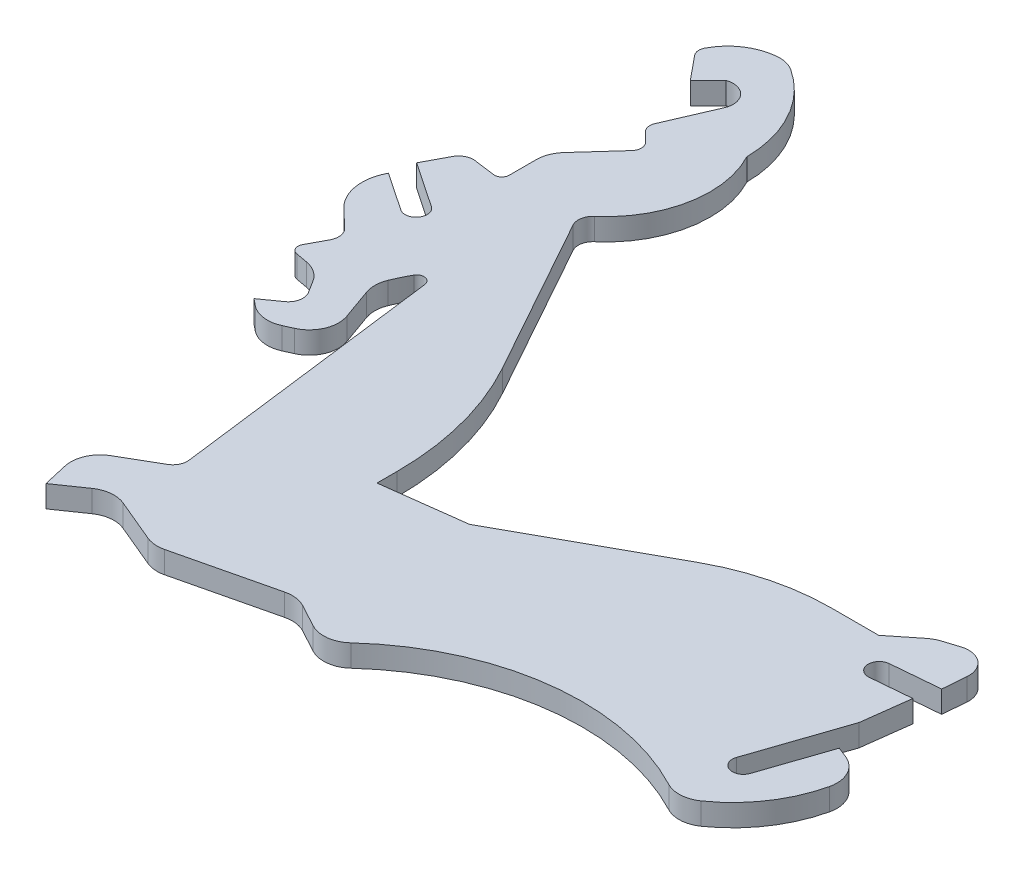
SolidWorks part; units mm, degrees
ref_plane "Front Plane" through (0, 0, 0) normal (0, 0, 1) x (1, 0, 0)
ref_plane "Top Plane" through (0, 0, 0) normal (0, 1, 0) x (1, 0, 0)
ref_plane "Right Plane" through (0, 0, 0) normal (1, 0, 0) x (0, 0, -1)
sketch "Sketch2" plane through (0, 0, 0) normal (0, 1, 0) x (1, 0, 0)
  line L0 (104.8617, 51.61) -> (96.2857, 51.61)
  line L1 (96.2857, 48.61) -> (104.8617, 48.61)
  line L2 (104.8617, 48.61) -> (104.8617, 42.36)
  line L3 (107.0706, 39.34) -> (104.0266, 29.4584)
  line L4 (101.1595, 30.3416) -> (104.8617, 42.36)
  line L5 (105.5312, 18.3607) -> (111.09, 27.1258)
  line L6 (104.8617, 51.61) -> (107.0706, 55.46)
  line L7 (89.7728, 69.8362) -> (57.4, 86.17)
  line L8 (41.6529, 73.6621) -> (36.03, 31.3784)
  line L9 (36.03, 31.3784) -> (29.1482, 28.9869)
  line L10 (29.1482, 28.9869) -> (21.9915, 21.0198)
  line L11 (21.9915, 21.0198) -> (8.1869, 15.1615)
  line L12 (0, 0) -> (0, 4.28)
  line L13 (0, 4.28) -> (8.2554, 5.2)
  line L14 (7.9231, 8.1815) -> (-3.1214, 6.9507)
  line L15 (-3.1214, 6.9507) -> (-7.4992, 8.4826)
  line L16 (-7.4992, 8.4826) -> (-11.8276, 7.2216)
  line L17 (-11.8276, 7.2216) -> (-19.2552, 11.2976)
  line L18 (-19.2552, 11.2976) -> (-23.2053, 10.8574)
  line L19 (-23.2053, 10.8574) -> (-22.2697, 7.6463)
  line L20 (-22.2697, 7.6463) -> (-24.8125, 7.2216)
  line L21 (0, 0) -> (20.16, 0)
  line L22 (20.16, 0) -> (27.0155, 3.9247)
  line L23 (27.0155, 3.9247) -> (38.9, -1.2)
  line L24 (38.9, -1.2) -> (41.66, 2.4827)
  line L25 (41.66, 2.4827) -> (45.9, 1.9915)
  line L26 (45.9, 1.9915) -> (46.4657, 5.8541)
  line L27 (25.83, 11.99) -> (49.95, 19.39)
  line L28 (49.95, 19.39) -> (57.13, 16.32)
  line L29 (57.13, 16.32) -> (61.9358, 23.0276)
  line L30 (61.9358, 23.0276) -> (67.6517, 44.29)
  arc A0 (96.2857, 51.61) -> (96.2857, 48.61) centre (96.2857, 50.11) ccw
  arc A1 (107.0706, 39.34) -> (111.09, 27.1258) centre (97.2099, 29.3266) cw
  arc A2 (104.0266, 29.4584) -> (101.1595, 30.3416) centre (102.5931, 29.9) cw
  arc A3 (107.0706, 55.46) -> (93.2591, 66.4439) centre (93.6334, 52.7391) ccw
  arc A4 (93.2591, 66.4439) -> (89.7728, 69.8362) centre (93.1665, 69.8362) cw
  arc A5 (57.4, 86.17) -> (41.6529, 73.6621) centre (56.0104, 71.7528) ccw
  arc A6 (8.1869, 15.1615) -> (-17.7049, 14.5311) centre (-5.6083, 49.7338) cw
  arc A7 (8.2554, 5.2) -> (7.9231, 8.1815) centre (8.0892, 6.6908) ccw
  arc A8 (-24.8125, 7.2216) -> (-27.5, 15.12) centre (-19.6156, 13.3963) cw
  arc A9 (-27.5, 15.12) -> (-17.7049, 14.5311) centre (-22.91, 9.71) cw
  arc A10 (46.4657, 5.8541) -> (26.4315, 9.0647) centre (30.5748, -29.1928) ccw
  arc A11 (26.4315, 9.0647) -> (25.83, 11.99) centre (26.27, 10.556) cw
  arc A12 (67.6517, 44.29) -> (105.5312, 18.3607) centre (122.4523, 83.7134) ccw
  point P4 (0, 0)
  point P9 (102.1515, 28.4665)
  point P12 (94.7857, 50.11)
  point P13 (-27.5, 15.12)
  point P72 (9.58, 6.8569)
  dimension "D6" = 1.5
  dimension "D11" = 1.5
  dimension "D32" = 14.0535
  dimension "D33" = 13.7098
  dimension "D34" = 3.3937
  dimension "D35" = 14.484
  dimension "D36" = 37.223
  dimension "D37" = 8.0706
  dimension "D38" = 7.0948
  dimension "D39" = 38.4812
  dimension "D40" = 67.5078
  dimension "D75" = 1.5
  dimension "D1" = 51.61
  dimension "D2" = 111.09
  dimension "D3" = 10.076
  dimension "D4" = 27.5
  dimension "D5" = 15.12
  dimension "D7" = 29.9
  dimension "D8" = 39.34
  dimension "D9" = 6.25
  dimension "D10" = 102.5931
  dimension "D12" = 4.28
  dimension "D13" = 20.16
  dimension "D14" = 5.14
  dimension "D15" = 1.2
  dimension "D16" = 45.9
  dimension "D17" = 38.9
  dimension "D18" = 86.17
  dimension "D19" = 9.58
  dimension "D20" = 5.2
  dimension "D21" = 11.99
  dimension "D22" = 16.32
  dimension "D23" = 57.13
  dimension "D24" = 49.95
  dimension "D25" = 26.27
  dimension "19.39" = 19.39
  dimension "D26" = 84.9
  dimension "D27" = 63.53
  dimension "D28" = 37.21
  dimension "D29" = 44.29
  dimension "D30" = 3.85
  dimension "D31" = 20
  dimension "D41" = 8.1869
  dimension "D42" = 21.9915
  dimension "D43" = 26.4315
  dimension "D44" = 27.0155
  dimension "D45" = 29.1482
  dimension "D46" = 41.6529
  dimension "D47" = 41.66
  dimension "D48" = 46.4657
  dimension "D49" = 56.0104
  dimension "D50" = 61.9358
  dimension "D51" = 67.6517
  dimension "D52" = 89.7728
  dimension "D53" = 97.2099
  dimension "D54" = 105.5312
  dimension "D55" = 122.4523
  dimension "D56" = 3.1214
  dimension "D57" = 5.6083
  dimension "D58" = 7.4992
  dimension "D59" = 11.8276
  dimension "D60" = 17.7049
  dimension "D61" = 19.2552
  dimension "D62" = 19.6156
  dimension "D63" = 22.2697
  dimension "D64" = 22.91
  dimension "D65" = 23.2053
  dimension "D66" = 24.8125
  dimension "D67" = 1.9915
  dimension "D68" = 2.4827
  dimension "D69" = 7.6463
  dimension "D70" = 8.4826
  dimension "D71" = 11.2976
  dimension "D72" = 21.0198
  dimension "D73" = 23.0276
  dimension "D74" = 28.9869
sketch "Sketch3" plane through (0, 0, 0) normal (0, 1, 0) x (1, 0, 0)
  line L0 (7.9231, 8.1815) -> (1.2884, 7.4422)
  line L1 (45.9, 1.9915) -> (46.4657, 5.8541) construction
  line L2 (41.66, 2.4827) -> (45.9, 1.9915) construction
  line L3 (38.9, -1.2) -> (41.66, 2.4827) construction
  line L4 (27.0155, 3.9247) -> (38.9, -1.2) construction
  line L5 (20.16, 0) -> (27.0155, 3.9247) construction
  line L6 (0, 4.28) -> (8.2554, 5.2) construction
  line L7 (0, 0) -> (0, 4.28) construction
  line L8 (0, 0) -> (20.16, 0) construction
  line L9 (1.2884, 7.4422) -> (2.7682, 14.19)
  line L10 (45.9, 1.9915) -> (46.4657, 5.8541)
  line L11 (41.66, 2.4827) -> (45.9, 1.9915)
  line L12 (38.9, -1.2) -> (41.66, 2.4827)
  line L13 (27.0155, 3.9247) -> (38.9, -1.2)
  line L14 (20.16, 0) -> (27.0155, 3.9247)
  line L15 (0, 4.28) -> (8.2554, 5.2)
  line L16 (0, 0) -> (0, 4.28)
  line L17 (0, 0) -> (20.16, 0)
  line L18 (-19.3597, 16.8) -> (-22.2168, 13.6663)
  line L19 (-22.2168, 13.6663) -> (-24.8203, 14.623)
  line L20 (-24.8203, 14.623) -> (-22.6465, 20.5386)
  line L21 (-22.6465, 20.5386) -> (-15.7038, 22.1118)
  line L22 (-15.7038, 22.1118) -> (-10.0733, 18.8185)
  line L23 (-10.0733, 18.8185) -> (-5.1865, 19.8808)
  line L24 (-5.1865, 19.8808) -> (12.13, 16.8)
  line L25 (12.13, 16.8) -> (38.76, 34.29)
  line L26 (87.31, 93.5914) -> (80.7227, 93.015)
  line L27 (80.9841, 90.0265) -> (86.4632, 90.5058)
  line L28 (87.31, 93.5914) -> (87.31, 111.63)
  line L29 (87.31, 111.63) -> (66.29, 103.0079)
  line L32 (66.29, 103.0079) -> (64.5523, 69.7569)
  line L33 (64.5523, 69.7569) -> (56.0586, 66.407)
  line L34 (56.0586, 66.407) -> (44.7, 32)
  line L35 (44.7, 32) -> (38.76, 34.29)
  line L36 (25.83, 11.99) -> (54.05, 24.15)
  line L37 (54.05, 24.15) -> (66.29, 24.15)
  line L38 (68.0387, 28.663) -> (60.2978, 29.686)
  line L39 (87.31, 79.61) -> (91.6185, 77.8876)
  line L40 (87.31, 79.61) -> (84.2303, 70.5437)
  line L41 (81.3897, 71.5086) -> (85.6329, 84)
  line L42 (85.6329, 84) -> (86.4632, 90.5058)
  arc A0 (25.83, 11.99) -> (26.4315, 9.0647) centre (26.27, 10.556) ccw construction
  arc A1 (46.4657, 5.8541) -> (26.4315, 9.0647) centre (30.5748, -29.1928) ccw construction
  arc A3 (25.83, 11.99) -> (26.4315, 9.0647) centre (26.27, 10.556) ccw
  arc A4 (46.4657, 5.8541) -> (26.4315, 9.0647) centre (30.5748, -29.1928) ccw
  arc A5 (8.2554, 5.2) -> (7.9231, 8.1815) centre (8.0892, 6.6908) ccw
  arc A6 (2.7682, 14.19) -> (-19.3597, 16.8) centre (-1.1426, 76.1401) cw
  arc A7 (80.7227, 93.015) -> (80.9841, 90.0265) centre (80.8534, 91.5207) ccw
  arc A8 (66.29, 24.15) -> (68.0387, 28.663) centre (61.3409, 28.663) ccw
  arc A9 (60.2978, 29.686) -> (80.9841, 62.2084) centre (34.8127, 68.7363) ccw
  arc A10 (91.6185, 77.8876) -> (80.9841, 62.2084) centre (74.0824, 78.3355) cw
  arc A11 (84.2303, 70.5437) -> (81.3897, 71.5086) centre (82.81, 71.0261) cw
  point P20 (87.31, 111.63)
  point P28 (87.31, 79.61)
  point P40 (79.3591, 91.39)
  point P55 (0, 2.14)
  point P77 (9.58, 6.8569)
  point P90 (82.3275, 69.6058)
  dimension "D5" = 1.5
  dimension "D22" = 62.0734
  dimension "D23" = 6.6978
  dimension "D24" = 46.6306
  dimension "D25" = 17.5418
  dimension "D1" = 111.63
  dimension "D2" = 87.31
  dimension "D3" = 79.61
  dimension "D4" = 17.97
  dimension "D6" = 8.25
  dimension "95" = 95
  dimension "D7" = 54.05
  dimension "D8" = 44.7
  dimension "D9" = 32
  dimension "D10" = 24.15
  dimension "D11" = 16.8
  dimension "D12" = 2.55
  dimension "D13" = 38.76
  dimension "D14" = 2.29
  dimension "D15" = 66.29
  dimension "D16" = 4.64
  dimension "D17" = 23.46
  dimension "D18" = 82.81
  dimension "D19" = 84
  dimension "D20" = 5.5
  dimension "D21" = 14.19
  dimension "D26" = 1.2884
  dimension "D27" = 2.7682
  dimension "D28" = 34.8127
  dimension "D29" = 56.0586
  dimension "D30" = 60.2978
  dimension "D31" = 61.3409
  dimension "D32" = 64.5523
  dimension "D33" = 68.0387
  dimension "D34" = 74.0824
  dimension "D35" = 1.1426
  dimension "D36" = 13.6663
  dimension "D37" = 14.623
  dimension "D38" = 91.6185
  dimension "D39" = 18.8185
  dimension "D40" = 5.1865
  dimension "D41" = 10.0733
  dimension "D42" = 15.7038
  dimension "D43" = 19.8808
  dimension "D44" = 22.2168
  dimension "D45" = 22.6465
  dimension "D46" = 24.8203
  dimension "D48" = 22.1118
  dimension "D49" = 66.407
  dimension "D51" = 69.7569
  dimension "D53" = 103.0079
sketch "Sketch4" plane through (0, 0, 0) normal (0, 1, 0) x (1, 0, 0)
  line L0 (87.31, 79.61) -> (91.6185, 77.8876) construction
  line L1 (87.31, 79.61) -> (84.2303, 70.5437) construction
  line L2 (81.3897, 71.5086) -> (85.6329, 84) construction
  line L3 (85.6329, 84) -> (86.4632, 90.5058) construction
  line L4 (87.31, 93.5914) -> (80.7227, 93.015) construction
  line L5 (80.9841, 90.0265) -> (86.4632, 90.5058) construction
  line L6 (87.31, 79.61) -> (91.6185, 77.8876)
  line L7 (87.31, 79.61) -> (84.2303, 70.5437)
  line L8 (81.3897, 71.5086) -> (85.6329, 84)
  line L9 (85.6329, 84) -> (86.4632, 90.5058)
  line L10 (87.31, 93.5914) -> (80.7227, 93.015)
  line L11 (80.9841, 90.0265) -> (86.4632, 90.5058)
  line L12 (87.31, 93.5914) -> (87.9384, 101.2314)
  line L13 (87.9384, 101.2314) -> (80.8847, 99.0137)
  line L14 (80.8847, 99.0137) -> (76.6618, 95.6406)
  line L15 (76.6618, 95.6406) -> (62.4514, 95.6406)
  line L16 (62.4514, 95.6406) -> (35.6224, 80.8332)
  line L17 (35.6224, 80.8332) -> (24.4232, 79.3958)
  line L18 (24.4232, 79.3958) -> (24.4232, 92.5302)
  line L19 (24.4232, 92.5302) -> (6.4632, 124.7958)
  line L20 (39.5557, 56.754) -> (32.4992, 60.5705)
  line L21 (32.4992, 60.5705) -> (16.5173, 56.754)
  line L22 (16.5173, 56.754) -> (7.4148, 60.5705)
  line L23 (7.4148, 60.5705) -> (1.8925, 56.754)
  line L24 (1.8925, 56.754) -> (0.4632, 62.9924)
  line L25 (0.4632, 62.9924) -> (9.066, 67.9678)
  line L26 (9.066, 67.9678) -> (3.8794, 108.8404)
  line L27 (0.6632, 102.6159) -> (3.8794, 93.5914)
  line L28 (3.8794, 93.5914) -> (-2.9368, 90.5058)
  line L29 (-2.9368, 90.5058) -> (-5.7689, 92.8083)
  line L30 (-5.7689, 92.8083) -> (-1.7781, 95.6406)
  line L31 (-1.7781, 95.6406) -> (-4.7653, 100.4083)
  line L32 (-4.7653, 100.4083) -> (-9.4961, 101.2694)
  line L33 (-9.4961, 101.2694) -> (-6.8152, 106.2905)
  line L34 (-6.8152, 106.2905) -> (-13.5555, 112.677)
  line L35 (-13.5555, 112.677) -> (-11.4183, 116.8058)
  line L36 (-11.4183, 116.8058) -> (-6.2216, 113.3058)
  line L37 (-4.5458, 115.7941) -> (-10.725, 119.9558)
  line L38 (-10.725, 119.9558) -> (-8.366, 124.3875)
  line L39 (-8.366, 124.3875) -> (-2.9368, 123.667)
  line L40 (-2.9368, 123.667) -> (-2.9368, 130.0558)
  line L41 (-2.9368, 130.0558) -> (3.4131, 137.0856)
  line L42 (3.4131, 137.0856) -> (0.5228, 139.9564)
  line L43 (0.5228, 139.9564) -> (3.6981, 147.3182)
  line L44 (0.6632, 150.8114) -> (-1.7781, 148.37)
  line L45 (-1.7781, 148.37) -> (-4.9998, 152.3019)
  arc A0 (-6.2216, 113.3058) -> (-4.5458, 115.7941) centre (-5.3837, 114.5499) ccw
  arc A1 (81.3897, 71.5086) -> (84.2303, 70.5437) centre (82.81, 71.0261) ccw construction
  arc A2 (80.7227, 93.015) -> (80.9841, 90.0265) centre (80.8534, 91.5207) ccw construction
  arc A3 (91.6185, 77.8876) -> (81.8558, 62.61) centre (74.0824, 78.3355) cw
  arc A4 (81.3897, 71.5086) -> (84.2303, 70.5437) centre (82.81, 71.0261) ccw
  arc A5 (80.7227, 93.015) -> (80.9841, 90.0265) centre (80.8534, 91.5207) ccw
  arc A6 (80.9841, 62.2084) -> (91.6185, 77.8876) centre (74.0824, 78.3355) ccw construction
  arc A7 (81.8558, 62.61) -> (39.5557, 56.754) centre (64.2679, 33.9509) ccw
  arc A8 (3.8794, 108.8404) -> (0.6632, 102.6159) centre (21.1237, 95.9873) ccw
  arc A9 (6.4632, 124.7958) -> (11.0968, 143.2092) centre (-1.4543, 136.5779) ccw
  arc A10 (11.0968, 143.2092) -> (2.7832, 157.1114) centre (-4.9998, 143.0202) ccw
  arc A11 (3.6981, 147.3182) -> (0.6632, 150.8114) centre (1.4835, 148.4591) ccw
  arc A12 (-4.9998, 152.3019) -> (2.7832, 157.1114) centre (1.9469, 149.7625) cw
  point P0 (91.6185, 77.8876)
  point P22 (2.7832, 157.1114)
  point P24 (0.6632, 150.8114)
  point P25 (-2.9368, 90.5058)
  point P26 (24.4232, 79.3958)
  point P27 (6.4632, 124.7958)
  point P31 (37.6632, 57.2558)
  point P70 (-2.9368, 130.365)
  point P71 (-2.9368, 130.0558)
  point P72 (-13.5555, 112.677)
  point P74 (5.2836, 108.8946)
  point P75 (8.4935, 71.0261)
  point P76 (9.066, 67.9678)
  point P77 (12.229, 60.1104)
  point P78 (7.7636, 59.0479)
  point P79 (16.8662, 55.2315)
  point P80 (0, 0)
  point P81 (0, 0)
  point P82 (35.6224, 80.8332)
  point P83 (3.8794, 106.2905)
  point P85 (0, 0)
  point P86 (5.0821, 105.6005)
  point P87 (0.4632, 100.4083)
  point P88 (3.8794, 108.8404)
  point P89 (0.5228, 102.6159)
  point P90 (0, 0)
  dimension "D18" = 0.5228
  dimension "D22" = 33.6255
  dimension "D23" = 21.5075
  dimension "D24" = 14.1952
  dimension "D25" = 16.0977
  dimension "D26" = 2.4912
  dimension "D27" = 7.3963
  dimension "D1" = 7.64
  dimension "D2" = 62.04
  dimension "D3" = 11.11
  dimension "D4" = 34.29
  dimension "D5" = 80
  dimension "D6" = 63.52
  dimension "D7" = 83.68
  dimension "D8" = 2.12
  dimension "D9" = 6.3
  dimension "D10" = 17
  dimension "D11" = 48.8
  dimension "D12" = 33.25
  dimension "D13" = 89.4
  dimension "D14" = 3.65
  dimension "D15" = 26.3
  dimension "D16" = 29.45
  dimension "D17" = 7.45
  dimension "D19" = 22.8
  dimension "D20" = 86
  dimension "D21" = 6.4
  dimension "D28" = 1.4835
  dimension "D29" = 1.8925
  dimension "D30" = 1.9469
  dimension "D31" = 3.4131
  dimension "D32" = 3.6981
  dimension "D33" = 3.8794
  dimension "D34" = 7.4148
  dimension "D35" = 9.066
  dimension "D36" = 11.0968
  dimension "D37" = 16.5173
  dimension "D38" = 21.1237
  dimension "D39" = 32.4992
  dimension "D40" = 35.6224
  dimension "D41" = 39.5557
  dimension "D42" = 62.4514
  dimension "D43" = 64.2679
  dimension "D44" = 76.6618
  dimension "D45" = 80.8847
  dimension "D46" = 87.9384
  dimension "D47" = 1.4543
  dimension "D48" = 1.7781
  dimension "D49" = 4.5458
  dimension "D50" = 4.7653
  dimension "D51" = 60.5705
  dimension "D52" = 67.9678
  dimension "D53" = 5.7689
  dimension "D54" = 80.8332
  dimension "D55" = 6.8152
  dimension "D56" = 8.366
  dimension "D57" = 9.4961
  dimension "D58" = 92.5302
  dimension "D59" = 93.5914
  dimension "D60" = 13.5555
  dimension "D61" = 95.6406
  dimension "D62" = 95.9873
  dimension "D63" = 99.0137
  dimension "D64" = 100.4083
  dimension "D65" = 101.2694
  dimension "D67" = 106.2905
  dimension "D69" = 112.677
  dimension "D70" = 123.667
  dimension "D71" = 124.3875
  dimension "D72" = 130.0558
  dimension "D73" = 137.0856
  dimension "D74" = 139.9564
  dimension "D75" = 148.37
extrude "Boss-Extrude2" add sketch "Sketch4" along normal blind 3
fillet "Fillet1" radius 1 3 edges at (3.8794, 1.5, -108.8404) (-9.4961, 1.5, -101.2694) (-2.9368, 1.5, -123.667)
fillet "Fillet2" radius 4 14 edges at (81.8558, 1.5, -62.61) (0.4632, 1.5, -62.9924) (16.5173, 1.5, -56.754) (7.4148, 1.5, -60.5705) (32.4992, 1.5, -60.5705) (39.5557, 1.5, -56.754) (-2.9368, 1.5, -130.0558) (-4.7653, 1.5, -100.4083) (0.6632, 1.5, -102.6159) (-2.9368, 1.5, -90.5058) (3.8794, 1.5, -93.5914) (80.8847, 1.5, -99.0137) (91.6185, 1.5, -77.8876) (2.7832, 1.5, -157.1114)
fillet "Fillet3" radius 40 1 edges at (24.4232, 1.5, -92.5302)
fillet "Fillet4" radius 2 5 edges at (-6.8152, 1.5, -106.2905) (-1.7781, 1.5, -95.6406) (9.066, 1.5, -67.9678) (-8.366, 1.5, -124.3875) (6.4632, 1.5, -124.7958)
fillet "Fillet5" radius 1.4 3 edges at (-4.9998, 1.5, -152.3019) (0.5228, 1.5, -139.9564) (3.4131, 1.5, -137.0856)
fillet "Fillet6" radius 30 1 edges at (62.4514, 1.5, -95.6406)
fillet "Fillet7" radius 3 1 edges at (87.9384, 1.5, -101.2314)
fillet "Fillet8" radius 6 1 edges at (-13.5555, 1.5, -112.677)
